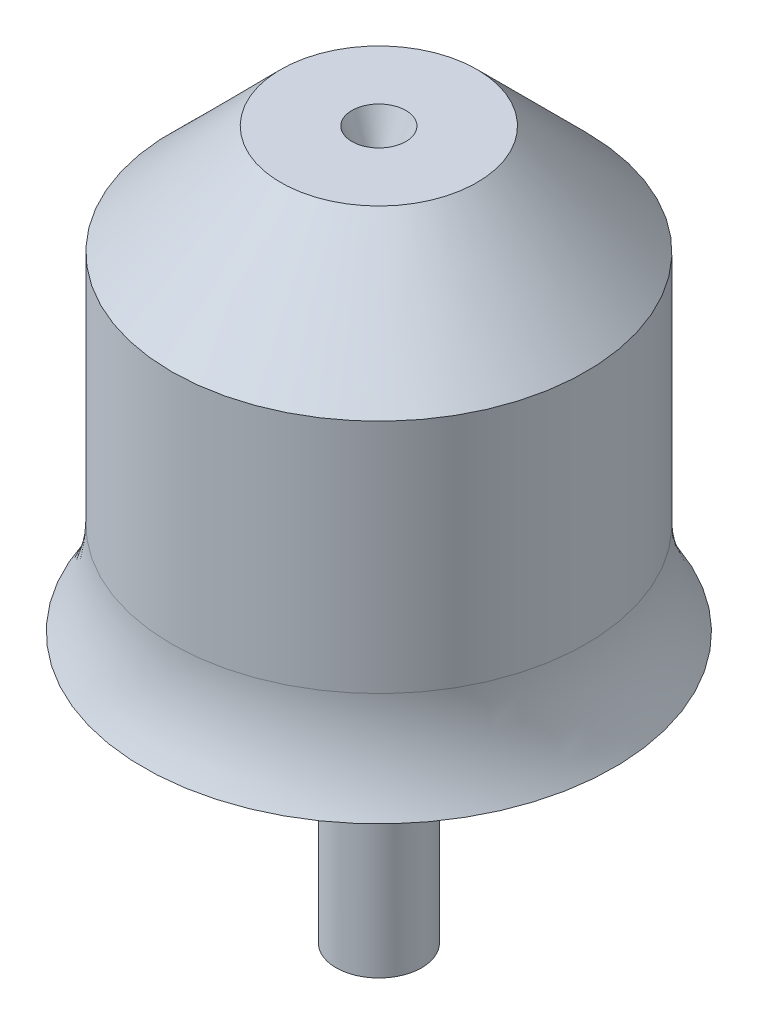
SolidWorks part; units mm, degrees
ref_plane "Front Plane" through (0, 0, 0) normal (0, 0, 1) x (1, 0, 0)
ref_plane "Top Plane" through (0, 0, 0) normal (0, 1, 0) x (1, 0, 0)
ref_plane "Right Plane" through (0, 0, 0) normal (1, 0, 0) x (0, 0, -1)
sketch "Sketch2" plane through (0, 0, 0) normal (0, 1, 0) x (1, 0, 0)
  circle A0 centre (0, 0) radius 6.35
  dimension "D1" = 12.7
extrude "Boss-Extrude1" add sketch "Sketch2" along normal blind 40
sketch "Sketch4" plane through (0, 0, 0) normal (0, 0, 1) x (1, 0, 0)
  line L0 (0, 40) -> (0, 105) construction
  line L1 (6.35, 40) -> (-6.35, 40) construction
  line L2 (0, 40) -> (34.9039, 40)
  line L4 (0, 40) -> (0, 105)
  line L7 (30.75, 88.8) -> (30.75, 53.8)
  line L8 (0, 105) -> (14.55, 105)
  line L9 (14.55, 105) -> (30.75, 88.8)
  arc A1 (34.9039, 40) -> (30.75, 53.8) centre (55.75, 53.8) cw
  dimension "D5" = 25
  dimension "D1" = 135
  dimension "D2" = 65
  dimension "D4" = 35
  dimension "D6" = 30.75
  dimension "D7" = 13.8
revolve "Revolve1" add sketch "Sketch4" angle 360 about L4
fillet "Fillet1" radius 10 1 edges at (0, 40, 6.35)
sketch "Sketch5" plane through (0, 105, 0) normal (0, 1, 0) x (1, 0, 0)
  circle A0 centre (0, 0) radius 4
  dimension "D1" = 8
sketch "Sketch6" plane through (0, 0, 0) normal (0, 0, 1) x (1, 0, 0)
  line L0 (0, 105) -> (0, 19.4318) construction
  point P4 (0, 95)
  dimension "D1" = 10
loft "Cut-Loft1" cut profiles "Sketch6", "Sketch5"
